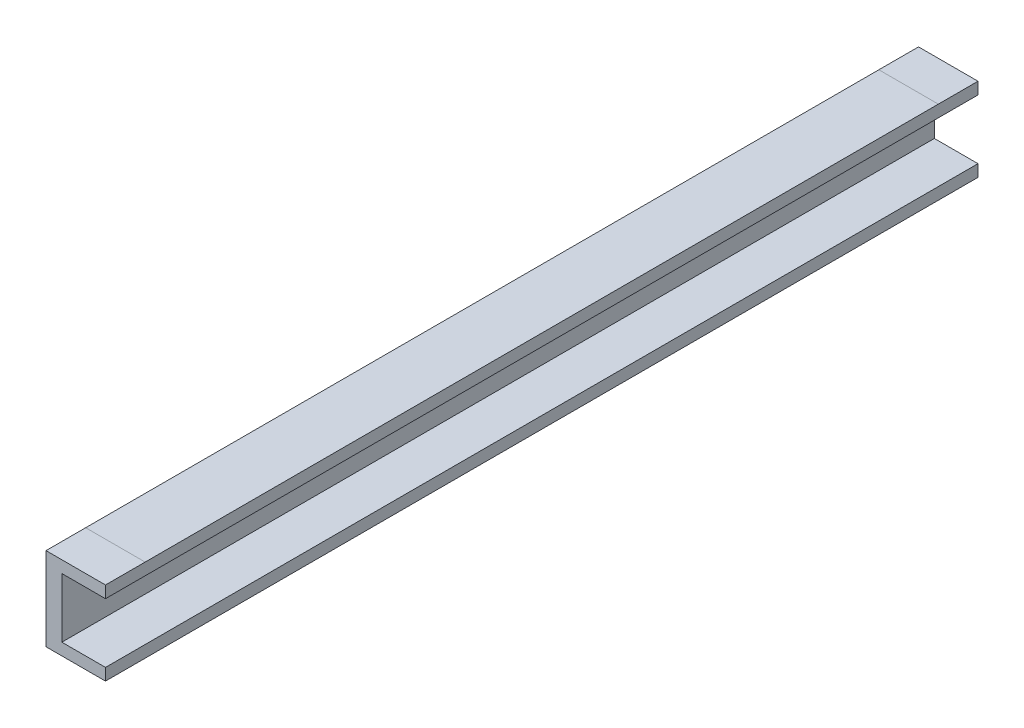
SolidWorks part; units mm, degrees
ref_plane "Płaszczyzna przednia" through (0, 0, 0) normal (0, 0, 1) x (1, 0, 0)
ref_plane "Płaszczyzna górna" through (0, 0, 0) normal (0, 1, 0) x (1, 0, 0)
ref_plane "Płaszczyzna prawa" through (0, 0, 0) normal (1, 0, 0) x (0, 0, -1)
sketch "Szkic1" plane through (0, 0, 0) normal (0, 0, 1) x (1, 0, 0)
  line L0 (0, 0) -> (0, 210)
  line L1 (0, 210) -> (150, 210)
  line L2 (150, 210) -> (150, 180)
  line L3 (150, 180) -> (40, 180)
  line L4 (40, 180) -> (40, 30)
  line L5 (40, 30) -> (150, 30)
  line L6 (150, 30) -> (150, 0)
  line L7 (150, 0) -> (0, 0)
  dimension "D1" = 210
  dimension "D2" = 150
  dimension "D3" = 150
  dimension "D4" = 110
extrude "Dodanie-wyciągnięcie1" add sketch "Szkic1" along normal blind 2200
sketch "Szkic3" plane through (0, 210, 0) normal (0, 1, 0) x (1, 0, 0)
  line L0 (0, -100) -> (150, -100)
  line L1 (0, -2200) -> (0, 0) construction
  line L2 (150, -2200) -> (150, 0) construction
  line L3 (0, -2100) -> (150, -2100)
  line L4 (150, -2200) -> (0, -2200) construction
  line L5 (150, 0) -> (0, 0) construction
  dimension "D1" = 100
  dimension "D2" = 100
split line "Linia podziałowa1"
